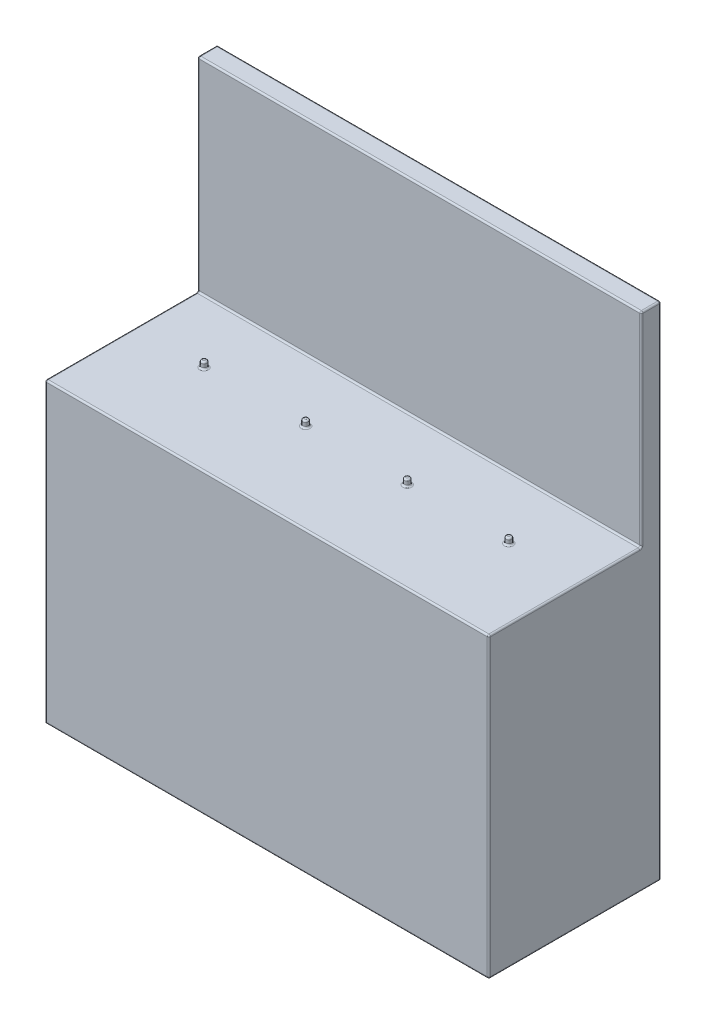
SolidWorks part; units mm, degrees
ref_plane "Front Plane" through (0, 0, 0) normal (0, 0, 1) x (1, 0, 0)
ref_plane "Top Plane" through (0, 0, 0) normal (0, 1, 0) x (1, 0, 0)
ref_plane "Right Plane" through (0, 0, 0) normal (1, 0, 0) x (0, 0, -1)
sketch "Sketch2" plane through (0, 0, 0) normal (0, 1, 0) x (1, 0, 0)
  line L1 (0, 0) -> (1354, 0)
  line L2 (0, 0) -> (0, 525)
  line L3 (0, 525) -> (1354, 525)
  line L4 (1354, 0) -> (1354, 525)
  dimension "D1" = 1354
  dimension "D2" = 525
extrude "Boss-Extrude1" add sketch "Sketch2" along normal blind 908
sketch "Sketch3" plane through (0, 908, 0) normal (0, 1, 0) x (1, 0, 0)
  line L0 (1354, 0) -> (1354, 525) construction
  line L1 (0, 525) -> (1354, 525)
  line L2 (0, 525) -> (0, 465.4)
  line L3 (0, 465.4) -> (1354, 465.4)
  line L4 (1354, 525) -> (1354, 465.4)
  dimension "D1" = 59.6
extrude "Boss-Extrude2" add sketch "Sketch3" along normal blind 622
sketch "Sketch4" plane through (0, 908, 0) normal (0, 1, 0) x (1, 0, 0)
  line L0 (0, 465.4) -> (0, 0) construction
  line L1 (1354, 525) -> (0, 525) construction
  circle A0 centre (210, 275) radius 8.5
  circle A1 centre (520, 275) radius 8.5
  circle A2 centre (830, 275) radius 8.5
  circle A3 centre (1140, 275) radius 8.5
  dimension "D1" = 17
  dimension "D2" = 17
  dimension "D3" = 17
  dimension "D4" = 17
  dimension "D5" = 210
  dimension "D6" = 520
  dimension "D7" = 830
  dimension "D8" = 1140
  dimension "D9" = 250
extrude "Boss-Extrude3" add sketch "Sketch4" along normal blind 20
fillet "Fillet2" radius 5 23 edges at (1140, 928, -266.5) (830, 928, -266.5) (520, 928, -266.5) (210, 928, -266.5) (0, 1530, -495.2) (677, 1530, -465.4) (1354, 1530, -495.2) (677, 1530, -525) (677, 0, 0) (1354, 0, -262.5) (677, 908, 0) (1354, 765, -525) (1354, 454, 0) (0, 454, 0) (210, 908, -283.5) (520, 908, -283.5) (830, 908, -283.5) (1140, 908, -283.5)
